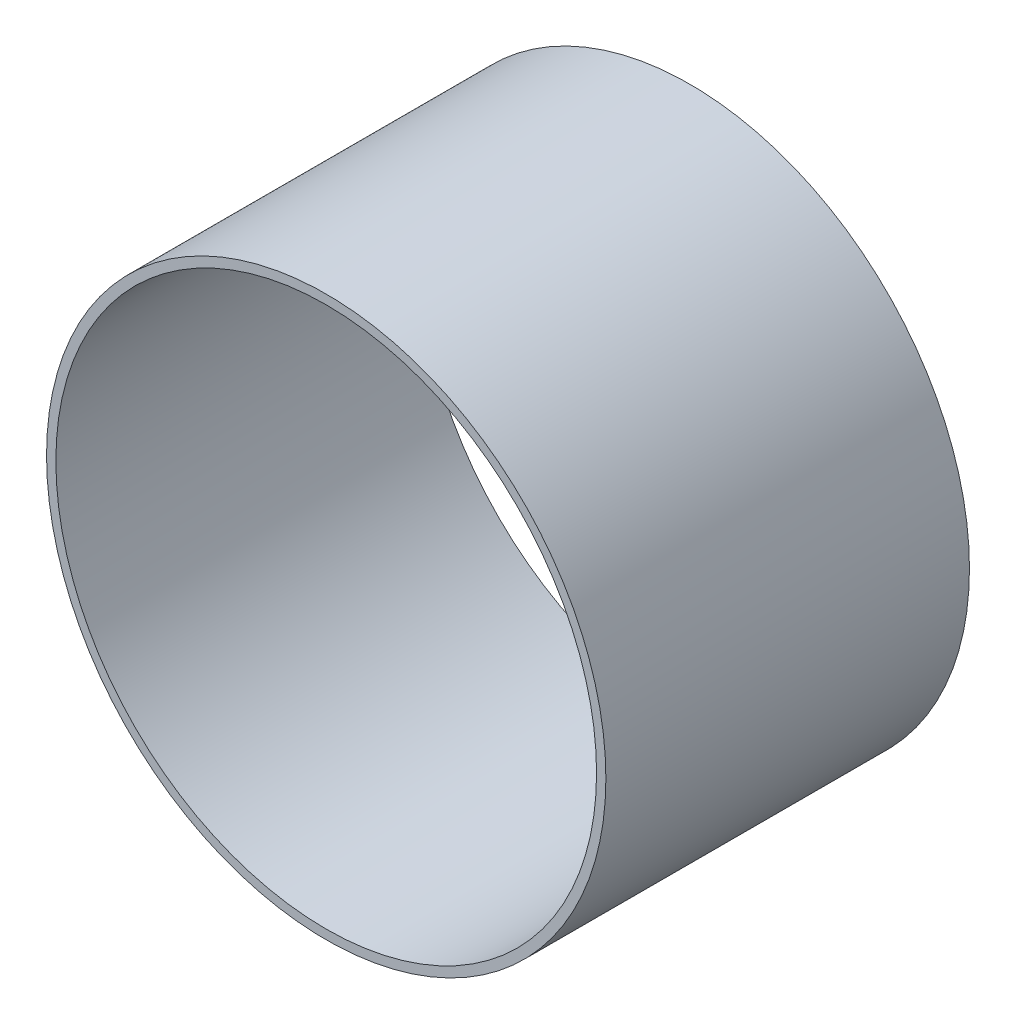
SolidWorks part; units mm, degrees
ref_plane "前视基准面" through (0, 0, 0) normal (0, 0, 1) x (1, 0, 0)
ref_plane "上视基准面" through (0, 0, 0) normal (0, 1, 0) x (1, 0, 0)
ref_plane "右视基准面" through (0, 0, 0) normal (1, 0, 0) x (0, 0, -1)
sketch "草图2" plane through (0, 0, 0) normal (0, 0, 1) x (1, 0, 0)
  circle A0 centre (0, 0) radius 87
  circle A1 centre (0, 0) radius 90
extrude "凸台-拉伸1" add sketch "草图2" along normal blind 117
